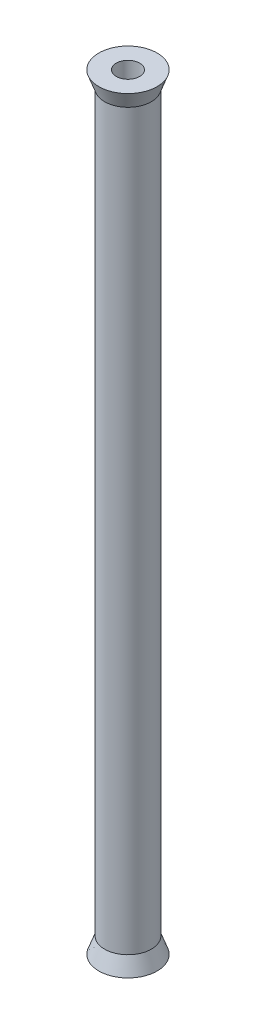
SolidWorks part; units mm, degrees
material "PET"
ref_plane "Front Plane" through (0, 0, 0) normal (0, 0, 1) x (1, 0, 0)
ref_plane "Top Plane" through (0, 0, 0) normal (0, 1, 0) x (1, 0, 0)
ref_plane "Right Plane" through (0, 0, 0) normal (1, 0, 0) x (0, 0, -1)
other "Configuration Table"
sketch "Sketch1" plane through (0, 0, 0) normal (0, 0, 1) x (1, 0, 0)
  line L0 (0, 0) -> (0, -50000) construction
  line L2 (2, -65.7) -> (5, -65.7)
  line L3 (2, 65.7) -> (5, 65.7)
  line L4 (4, -62.9525) -> (4, 62.9525)
  line L5 (2, 65.7) -> (2, -65.7)
  line L8 (5.5, 0) -> (-5.5, 0) construction
  line L9 (5, 65.7) -> (4, 62.9525)
  line L10 (5, -65.7) -> (4, -62.9525)
  point P4 (0, 0)
  dimension "Length" = 131.4
  dimension "D2" = 10
  dimension "D3" = 8
  dimension "ThreadDia" = 4
  dimension "D1" = 70
revolve "Revolve1" add sketch "Sketch1" angle 360 about L0
equation "\"D3@Sketch1\"= \"ThreadDia@Sketch1\" * 2"
equation "\"D2@Sketch1\"= \"ThreadDia@Sketch1\" * 2.5"
